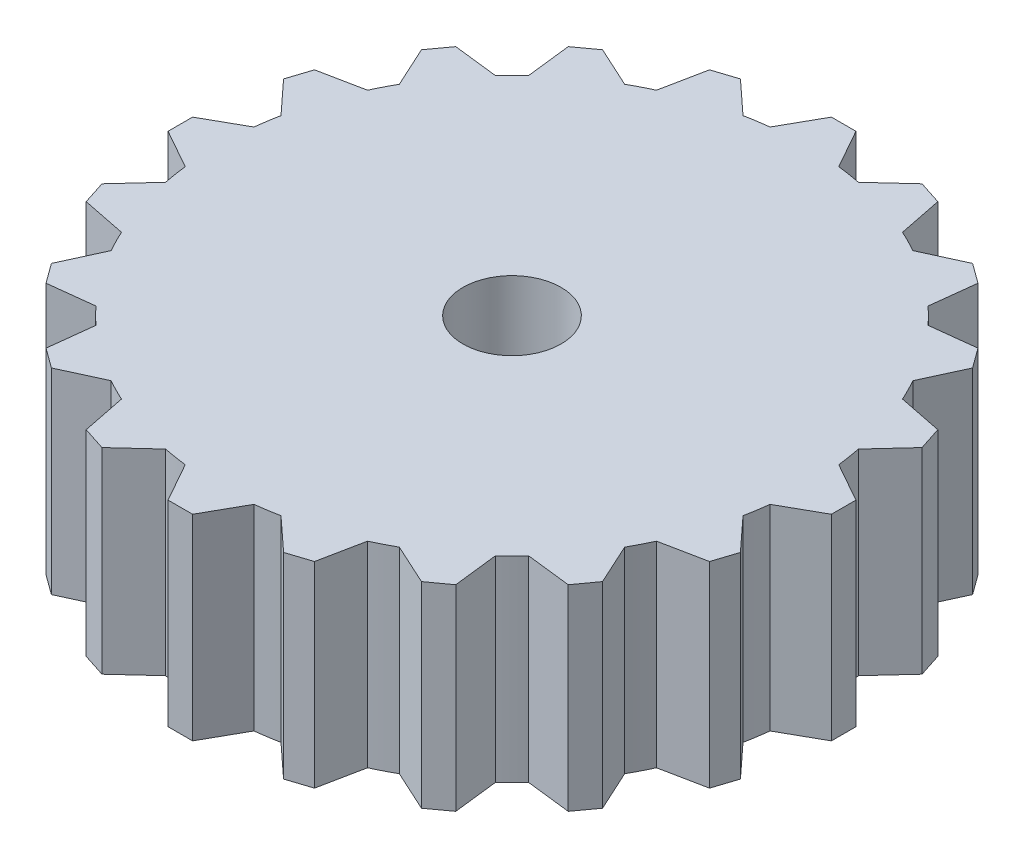
SolidWorks part; units mm, degrees
ref_plane "Front Plane" through (0, 0, 0) normal (0, 0, 1) x (1, 0, 0)
ref_plane "Top Plane" through (0, 0, 0) normal (0, 1, 0) x (1, 0, 0)
ref_plane "Right Plane" through (0, 0, 0) normal (1, 0, 0) x (0, 0, -1)
sketch "Sketch2" plane through (0, 0, 0) normal (0, 1, 0) x (1, 0, 0)
  line L0 (-0.625, 16.8976) -> (0.625, 16.8976)
  line L1 (-1.75, 14.8976) -> (-0.625, 16.8976)
  line L2 (2.9393, 14.7092) -> (4.6272, 16.2637)
  line L3 (1.75, 14.8976) -> (0.625, 16.8976)
  line L4 (4.6272, 16.2637) -> (5.816, 15.8774)
  line L5 (6.268, 13.6276) -> (5.816, 15.8774)
  line L6 (7.3408, 13.081) -> (9.4265, 14.0378)
  line L7 (9.4265, 14.0378) -> (10.4378, 13.3031)
  line L8 (10.1723, 11.0238) -> (10.4378, 13.3031)
  line L9 (11.0238, 10.1723) -> (13.3031, 10.4378)
  line L10 (13.3031, 10.4378) -> (14.0378, 9.4265)
  line L11 (13.081, 7.3408) -> (14.0378, 9.4265)
  line L12 (13.6276, 6.268) -> (15.8774, 5.816)
  line L13 (15.8774, 5.816) -> (16.2637, 4.6272)
  line L14 (14.7092, 2.9393) -> (16.2637, 4.6272)
  line L15 (14.8976, 1.75) -> (16.8976, 0.625)
  line L16 (16.8976, 0.625) -> (16.8976, -0.625)
  line L17 (14.8976, -1.75) -> (16.8976, -0.625)
  line L18 (14.7092, -2.9393) -> (16.2637, -4.6272)
  line L19 (16.2637, -4.6272) -> (15.8774, -5.816)
  line L20 (13.6276, -6.268) -> (15.8774, -5.816)
  line L21 (13.081, -7.3408) -> (14.0378, -9.4265)
  line L22 (14.0378, -9.4265) -> (13.3031, -10.4378)
  line L23 (11.0238, -10.1723) -> (13.3031, -10.4378)
  line L24 (10.1723, -11.0238) -> (10.4378, -13.3031)
  line L25 (10.4378, -13.3031) -> (9.4265, -14.0378)
  line L26 (7.3408, -13.081) -> (9.4265, -14.0378)
  line L27 (6.268, -13.6276) -> (5.816, -15.8774)
  line L28 (5.816, -15.8774) -> (4.6272, -16.2637)
  line L29 (2.9393, -14.7092) -> (4.6272, -16.2637)
  line L30 (1.75, -14.8976) -> (0.625, -16.8976)
  line L31 (0.625, -16.8976) -> (-0.625, -16.8976)
  line L32 (-1.75, -14.8976) -> (-0.625, -16.8976)
  line L33 (-2.9393, -14.7092) -> (-4.6272, -16.2637)
  line L34 (-4.6272, -16.2637) -> (-5.816, -15.8774)
  line L35 (-6.268, -13.6276) -> (-5.816, -15.8774)
  line L36 (-7.3408, -13.081) -> (-9.4265, -14.0378)
  line L37 (-9.4265, -14.0378) -> (-10.4378, -13.3031)
  line L38 (-10.1723, -11.0238) -> (-10.4378, -13.3031)
  line L39 (-11.0238, -10.1723) -> (-13.3031, -10.4378)
  line L40 (-13.3031, -10.4378) -> (-14.0378, -9.4265)
  line L41 (-13.081, -7.3408) -> (-14.0378, -9.4265)
  line L42 (-13.6276, -6.268) -> (-15.8774, -5.816)
  line L43 (-15.8774, -5.816) -> (-16.2637, -4.6272)
  line L44 (-14.7092, -2.9393) -> (-16.2637, -4.6272)
  line L45 (-14.8976, -1.75) -> (-16.8976, -0.625)
  line L46 (-16.8976, -0.625) -> (-16.8976, 0.625)
  line L47 (-14.8976, 1.75) -> (-16.8976, 0.625)
  line L48 (-14.7092, 2.9393) -> (-16.2637, 4.6272)
  line L49 (-16.2637, 4.6272) -> (-15.8774, 5.816)
  line L50 (-13.6276, 6.268) -> (-15.8774, 5.816)
  line L51 (-13.081, 7.3408) -> (-14.0378, 9.4265)
  line L52 (-14.0378, 9.4265) -> (-13.3031, 10.4378)
  line L53 (-11.0238, 10.1723) -> (-13.3031, 10.4378)
  line L54 (-10.1723, 11.0238) -> (-10.4378, 13.3031)
  line L55 (-10.4378, 13.3031) -> (-9.4265, 14.0378)
  line L56 (-7.3408, 13.081) -> (-9.4265, 14.0378)
  line L57 (-6.268, 13.6276) -> (-5.816, 15.8774)
  line L58 (-5.816, 15.8774) -> (-4.6272, 16.2637)
  line L59 (-2.9393, 14.7092) -> (-4.6272, 16.2637)
  arc A0 (-1.75, 14.8976) -> (-2.9393, 14.7092) centre (0, 0) ccw
  arc A1 (-10.1723, 11.0238) -> (-11.0238, 10.1723) centre (0, 0) ccw
  arc A2 (-6.268, 13.6276) -> (-7.3408, 13.081) centre (0, 0) ccw
  arc A3 (2.9393, 14.7092) -> (1.75, 14.8976) centre (0, 0) ccw
  arc A4 (7.3408, 13.081) -> (6.268, 13.6276) centre (0, 0) ccw
  arc A5 (11.0238, 10.1723) -> (10.1723, 11.0238) centre (0, 0) ccw
  arc A6 (13.6276, 6.268) -> (13.081, 7.3408) centre (0, 0) ccw
  arc A7 (14.8976, 1.75) -> (14.7092, 2.9393) centre (0, 0) ccw
  arc A8 (14.7092, -2.9393) -> (14.8976, -1.75) centre (0, 0) ccw
  arc A9 (13.081, -7.3408) -> (13.6276, -6.268) centre (0, 0) ccw
  arc A10 (10.1723, -11.0238) -> (11.0238, -10.1723) centre (0, 0) ccw
  arc A11 (6.268, -13.6276) -> (7.3408, -13.081) centre (0, 0) ccw
  arc A12 (1.75, -14.8976) -> (2.9393, -14.7092) centre (0, 0) ccw
  arc A13 (-2.9393, -14.7092) -> (-1.75, -14.8976) centre (0, 0) ccw
  arc A14 (-7.3408, -13.081) -> (-6.268, -13.6276) centre (0, 0) ccw
  arc A15 (-11.0238, -10.1723) -> (-10.1723, -11.0238) centre (0, 0) ccw
  arc A16 (-13.6276, -6.268) -> (-13.081, -7.3408) centre (0, 0) ccw
  arc A17 (-14.8976, -1.75) -> (-14.7092, -2.9393) centre (0, 0) ccw
  arc A18 (-14.7092, 2.9393) -> (-14.8976, 1.75) centre (0, 0) ccw
  arc A19 (-13.081, 7.3408) -> (-13.6276, 6.268) centre (0, 0) ccw
  point P5 (0, 16.8976)
  point P6 (0, 15)
  point P87 (0, 0)
  dimension "D1" = 30
  dimension "D2" = 3.5
  dimension "D3" = 1.75
  dimension "D4" = 1.25
  dimension "D5" = 2
  dimension "D6" = 2
  dimension "D7" = 20
extrude "Boss-Extrude2" add sketch "Sketch2" along normal blind 10
sketch "Sketch3" plane through (0, 0, 0) normal (0, -1, 0) x (1, 0, 0)
  circle A0 centre (0, 0) radius 10
  dimension "D1" = 20
extrude "Cut-Extrude1" cut sketch "Sketch3" against normal blind 2.2
sketch "Sketch4" plane through (0, 2.2, 0) normal (0, -1, 0) x (1, 0, 0)
  circle A0 centre (0, 0) radius 2.5
  dimension "D1" = 5
extrude "Cut-Extrude2" cut sketch "Sketch4" against normal through all contours A0
